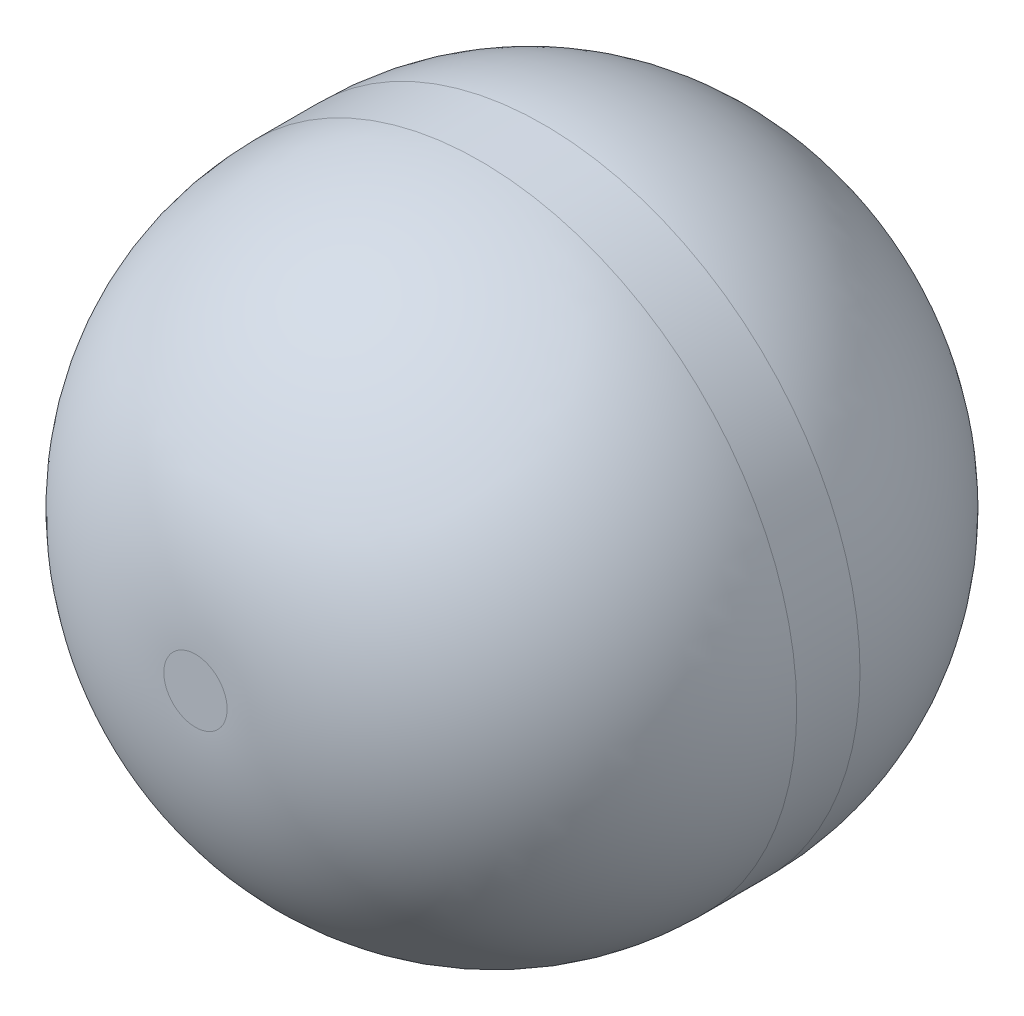
SolidWorks part; units mm, degrees
ref_plane "Front Plane" through (0, 0, 0) normal (0, 0, 1) x (1, 0, 0)
ref_plane "Top Plane" through (0, 0, 0) normal (0, 1, 0) x (1, 0, 0)
ref_plane "Right Plane" through (0, 0, 0) normal (1, 0, 0) x (0, 0, -1)
sketch "Sketch1" plane through (0, 0, 0) normal (0, 0, 1) x (1, 0, 0)
  circle A0 centre (0, 0) radius 50
  dimension "D1" = 100
extrude "Boss-Extrude1" add sketch "Sketch1" along normal mid plane 100
fillet "Fillet1" radius 45 2 edges at (50, 0, -50) (50, 0, 50)
